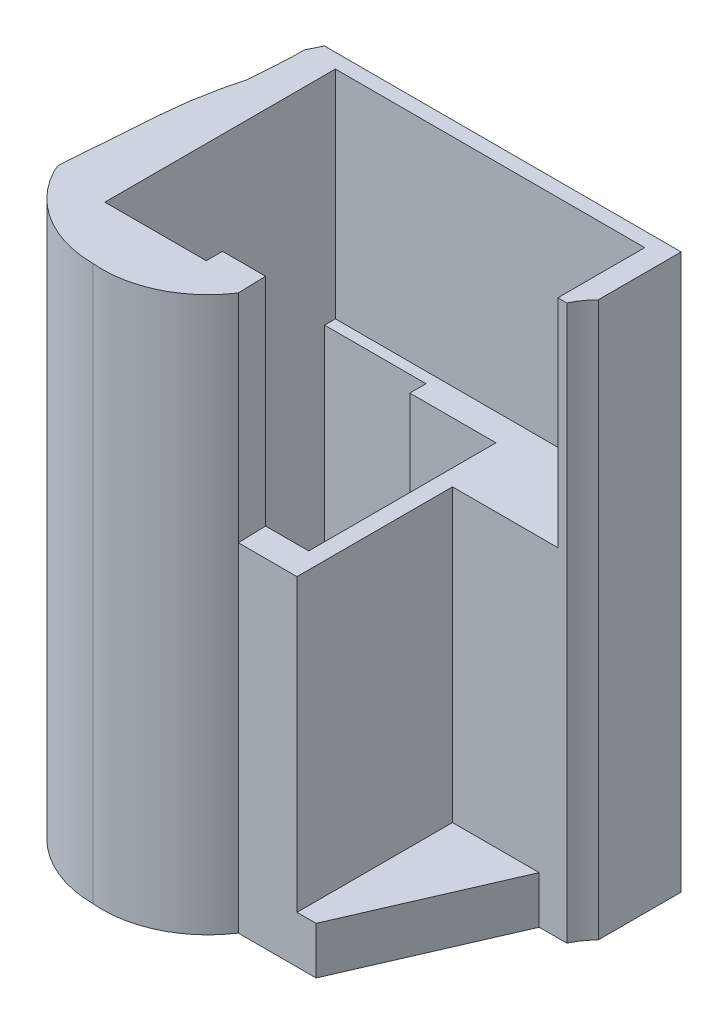
SolidWorks part; units mm, degrees
ref_plane "Front Plane" through (0, 0, 0) normal (0, 0, 1) x (1, 0, 0)
ref_plane "Top Plane" through (0, 0, 0) normal (0, 1, 0) x (1, 0, 0)
ref_plane "Right Plane" through (0, 0, 0) normal (1, 0, 0) x (0, 0, -1)
sketch "Sketch1" plane through (0, 0, 0) normal (0, 1, 0) x (1, 0, 0)
  line L0 (-21.9286, 20.53) -> (30.8194, 20.53)
  line L1 (30.8194, 20.53) -> (30.8194, 8.2695)
  line L2 (-21.9286, 20.53) -> (-22.9286, 18.53)
  line L3 (-22.9286, 18.53) -> (-22.9286, 16.53)
  line L4 (-22.9286, 16.53) -> (-23.3286, 10.53)
  line L5 (-23.3286, 10.53) -> (-24.1029, 7.4514)
  line L6 (-24.1029, 7.4514) -> (-24.8443, 3.4545)
  line L7 (-24.8443, 3.4545) -> (-25.2886, -0.5444)
  line L8 (-25.2886, -0.5444) -> (-26.3285, -14.47)
  line L9 (-26.3285, -14.47) -> (-25.9249, -15.432)
  line L10 (3.3204, -17.47) -> (14.82, -17.47)
  line L11 (14.82, -17.47) -> (24.8196, 5.53)
  line L12 (24.8196, 5.53) -> (28.8981, 5.53)
  arc A0 (-25.9249, -15.432) -> (-11.2183, -24.4463) centre (-11.1227, -7.7864) ccw
  arc A1 (-11.2183, -24.4463) -> (3.3204, -17.47) centre (-9.7241, -8.9225) ccw
  arc A2 (28.8981, 5.53) -> (30.8194, 8.2695) centre (37.5133, 1.5313) cw
extrude "Boss-Extrude1" add sketch "Sketch1" along normal blind 82
sketch "Sketch2" plane through (0, 0, 0) normal (0, -1, 0) x (1, 0, 0)
  line L0 (-18.1734, -16.7845) -> (-18.1734, 15.7155)
  line L1 (-18.1734, 15.7155) -> (-3.174, 15.7155)
  line L2 (-3.174, 15.7155) -> (-3.174, 13.3155)
  line L3 (-3.174, 13.3155) -> (9.5755, 13.3155)
  line L4 (9.5755, 13.3155) -> (9.5755, -14.3845)
  line L5 (9.5755, -14.3845) -> (-3.174, -14.3845)
  line L6 (-3.174, -14.3845) -> (-3.174, -16.7845)
  line L7 (-3.174, -16.7845) -> (-18.1734, -16.7845)
extrude "Cut-Extrude1" cut sketch "Sketch2" against normal blind 105
ref_plane "Plane1" through (40, 0, 0) normal (1, 0, 0) x (0, 0, -1)
sketch "Sketch7" plane through (40, 0, 0) normal (1, 0, 0) x (0, 0, -1)
  line L0 (-17.47, 0) -> (-17.47, 7) construction
  line L1 (-17.47, 82) -> (-17.47, 0) construction
  line L2 (-17.47, 7) -> (5.53, 7)
  line L3 (5.53, 82) -> (5.53, 0) construction
  line L4 (5.53, 7) -> (5.53, 50)
  line L5 (5.53, 82) -> (5.53, 0) construction
  line L6 (5.53, 50) -> (-17.47, 50)
  line L7 (-17.47, 50) -> (-17.47, 7)
extrude "Cut-Extrude3" cut sketch "Sketch7" against normal blind 28
ref_plane "Plane2" through (0, 90, 0) normal (0, 1, 0) x (1, 0, 0)
sketch "Sketch9" plane through (0, 82, 0) normal (0, 1, 0) x (1, 0, 0)
  line L0 (14.82, -17.47) -> (24.8196, 5.53)
  line L6 (14.82, -17.47) -> (15.3992, 5.53)
  line L7 (15.3992, 5.53) -> (24.8196, 5.53)
extrude "Cut-Extrude4" cut sketch "Sketch9" against normal blind 32
sketch "Sketch10" plane through (0, 82, 0) normal (0, 1, 0) x (1, 0, 0)
  line L0 (3.3204, -17.47) -> (3.2008, -13.3155)
  line L1 (-3.174, -13.3155) -> (9.5755, -13.3155) construction
  line L2 (3.2008, -13.3155) -> (9.5755, -13.3155)
  line L3 (9.5755, -13.3155) -> (9.5755, 14.3845)
  line L4 (9.5755, 14.3845) -> (9.5755, 18.3845)
  line L5 (9.5755, 18.3845) -> (27.5755, 18.3845)
  line L6 (27.5755, 18.3845) -> (27.5755, 9.3845)
  line L7 (3.3204, -17.47) -> (14.82, -17.47)
  line L8 (14.82, -17.47) -> (15.3992, 5.53)
  line L9 (15.3992, 5.53) -> (27.5755, 5.53)
  line L10 (15.3992, 5.53) -> (28.8981, 5.53) construction
  line L11 (27.5755, 5.53) -> (27.5755, 9.3845)
extrude "Cut-Extrude5" cut sketch "Sketch10" against normal blind 32
sketch "Sketch12" plane through (0, 82, 0) normal (0, 1, 0) x (1, 0, 0)
  line L0 (9.5755, 14.3845) -> (-3.174, 14.3845)
  line L1 (-3.174, 14.3845) -> (-3.174, 16.7845)
  line L2 (-3.174, 16.7845) -> (-18.1734, 16.7845)
  line L3 (9.5755, 14.3845) -> (9.5755, 18.3845)
  line L4 (9.5755, 18.3845) -> (-18.1734, 18.3845)
  line L5 (-18.1734, 18.3845) -> (-18.1734, 16.7845)
extrude "Cut-Extrude6" cut sketch "Sketch12" against normal blind 32
